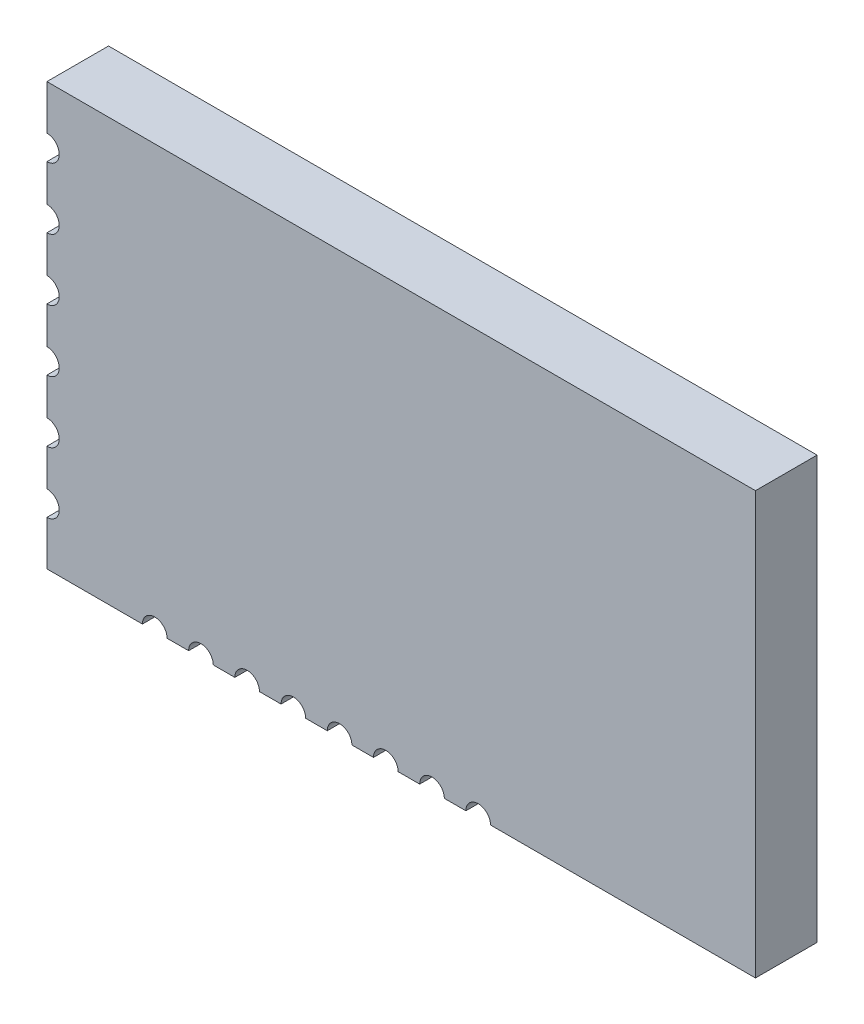
SolidWorks part; units mm, degrees
ref_plane "Спереди" through (0, 0, 0) normal (0, 0, 1) x (1, 0, 0)
ref_plane "Сверху" through (0, 0, 0) normal (0, 1, 0) x (1, 0, 0)
ref_plane "Справа" through (0, 0, 0) normal (1, 0, 0) x (0, 0, -1)
sketch "Эскиз1" plane through (0, 0, 0) normal (0, 0, -1) x (-1, 0, 0)
  line L0 (-4.0231, -1.9756) -> (-3.3231, -1.9756)
  line L1 (-13.4231, -1.9756) -> (-4.8231, -1.9756)
  line L2 (-13.4231, -1.9756) -> (-13.4231, 11.7244)
  line L3 (-13.4231, 11.7244) -> (9.5769, 11.7244)
  line L4 (9.5769, -1.9756) -> (9.5769, -0.5256)
  line L5 (-2.5231, -1.9756) -> (-1.8231, -1.9756)
  line L6 (-1.0231, -1.9756) -> (-0.3231, -1.9756)
  line L7 (0.4769, -1.9756) -> (1.1769, -1.9756)
  line L8 (1.9769, -1.9756) -> (2.6769, -1.9756)
  line L9 (3.4769, -1.9756) -> (4.1769, -1.9756)
  line L10 (4.9769, -1.9756) -> (5.6769, -1.9756)
  line L11 (6.4769, -1.9756) -> (9.5769, -1.9756)
  line L12 (9.5769, 0.2744) -> (9.5769, 1.4744)
  line L13 (9.5769, 2.2744) -> (9.5769, 3.4744)
  line L14 (9.5769, 4.2744) -> (9.5769, 5.4744)
  line L15 (9.5769, 6.2744) -> (9.5769, 7.4744)
  line L16 (9.5769, 8.2744) -> (9.5769, 9.4744)
  line L17 (9.5769, 10.2744) -> (9.5769, 11.7244)
  arc A0 (-4.0231, -1.9756) -> (-4.8231, -1.9756) centre (-4.4231, -1.9756) ccw
  arc A1 (-2.5231, -1.9756) -> (-3.3231, -1.9756) centre (-2.9231, -1.9756) ccw
  arc A2 (-1.0231, -1.9756) -> (-1.8231, -1.9756) centre (-1.4231, -1.9756) ccw
  arc A3 (0.4769, -1.9756) -> (-0.3231, -1.9756) centre (0.0769, -1.9756) ccw
  arc A4 (1.9769, -1.9756) -> (1.1769, -1.9756) centre (1.5769, -1.9756) ccw
  arc A5 (3.4769, -1.9756) -> (2.6769, -1.9756) centre (3.0769, -1.9756) ccw
  arc A6 (4.9769, -1.9756) -> (4.1769, -1.9756) centre (4.5769, -1.9756) ccw
  arc A7 (6.4769, -1.9756) -> (5.6769, -1.9756) centre (6.0769, -1.9756) ccw
  arc A9 (9.5769, 10.2744) -> (9.5769, 9.4744) centre (9.5769, 9.8744) ccw
  arc A15 (9.5769, 8.2744) -> (9.5769, 7.4744) centre (9.5769, 7.8744) ccw
  arc A16 (9.5769, 6.2744) -> (9.5769, 5.4744) centre (9.5769, 5.8744) ccw
  arc A17 (9.5769, 4.2744) -> (9.5769, 3.4744) centre (9.5769, 3.8744) ccw
  arc A18 (9.5769, 2.2744) -> (9.5769, 1.4744) centre (9.5769, 1.8744) ccw
  arc A19 (9.5769, 0.2744) -> (9.5769, -0.5256) centre (9.5769, -0.1256) ccw
  dimension "D3" = 0.8
  dimension "D5" = 8
  dimension "D7" = 1.85
  dimension "D6" = 0.8
  dimension "D8" = 6
  dimension "D1" = 13.7
  dimension "D2" = 23
  dimension "D4" = 9
extrude "Бобышка-Вытянуть1" add sketch "Эскиз1" along normal blind 2
